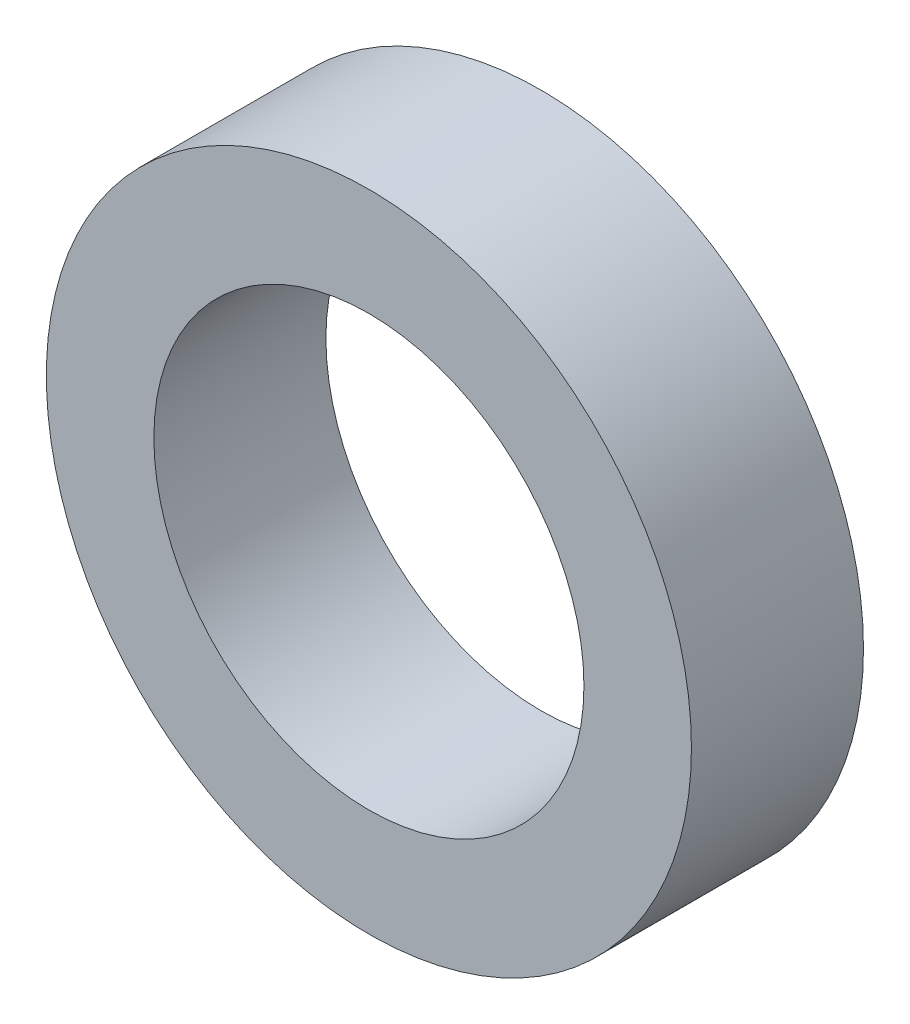
SolidWorks part; units mm, degrees
ref_plane "Front Plane" through (0, 0, 0) normal (0, 0, 1) x (1, 0, 0)
ref_plane "Top Plane" through (0, 0, 0) normal (0, 1, 0) x (1, 0, 0)
ref_plane "Right Plane" through (0, 0, 0) normal (1, 0, 0) x (0, 0, -1)
sketch "Sketch1" plane through (0, 0, 0) normal (0, 0, 1) x (1, 0, 0)
  circle A0 centre (0, 0) radius 5
  circle A1 centre (0, 0) radius 7.5
  dimension "D1" = 10
  dimension "D2" = 15
extrude "Boss-Extrude1" add sketch "Sketch1" along normal blind 4
